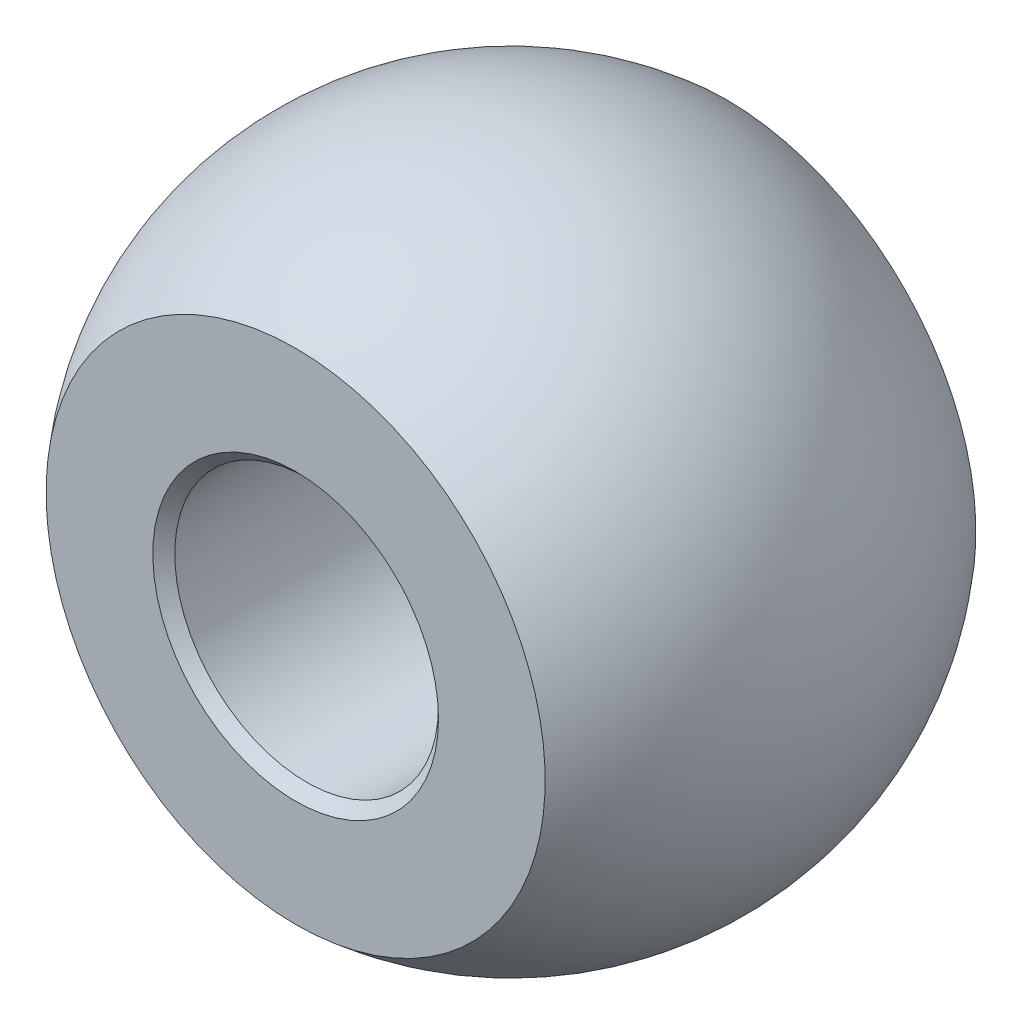
SolidWorks part; units mm, degrees
ref_plane "Front Plane" through (0, 0, 0) normal (0, 0, 1) x (1, 0, 0)
ref_plane "Top Plane" through (0, 0, 0) normal (0, 1, 0) x (1, 0, 0)
ref_plane "Right Plane" through (0, 0, 0) normal (1, 0, 0) x (0, 0, -1)
other "Center of Mass"
sketch "Sketch1" plane through (0, 0, 0) normal (0, 0, 1) x (1, 0, 0)
  line L0 (0, 0) -> (0, 7.5)
  arc A0 (0, 0) -> (0, 7.5) centre (0, 3.75) ccw
  dimension "D1" = 7.5
revolve "Revolve1" add sketch "Sketch1" angle 360 about L0
sketch "Sketch2" plane through (0, 0, 0) normal (1, 0, 0) x (0, 0, -1)
  line L0 (0, 0) -> (0, 1.219) construction
  line L1 (-4.45, 7.6) -> (-2.45, 7.6)
  line L2 (-4.45, 7.6) -> (-4.45, 0)
  line L3 (-4.45, 0) -> (-2.45, 0)
  line L4 (-2.45, 7.6) -> (-2.45, 0)
  line L5 (0.0734, 0) -> (5.1223, 0) construction
  line L6 (4.45, 0) -> (2.45, 0)
  line L7 (2.45, 7.6) -> (2.45, 0)
  line L8 (4.45, 7.6) -> (2.45, 7.6)
  line L9 (4.45, 7.6) -> (4.45, 0)
  dimension "D1" = 2.45
  dimension "D2" = 2
  dimension "D3" = 7.6
extrude "Cut-Extrude1" cut sketch "Sketch2" against normal through all both and the other way through all
sketch "Sketch3" plane through (0, 0, 2.45) normal (0, 0, 1) x (1, 0, 0)
  circle A0 centre (0, 3.75) radius 1.5
  circle A1 centre (0, 3.75) radius 2.839 construction
  dimension "D1" = 3
extrude "Cut-Extrude2" cut sketch "Sketch3" against normal through all both
chamfer "Chamfer1" distance 0.125 angle 45 2 edges at (1.5, 3.75, -2.45) (1.5, 3.75, 2.45)
ref_point "Point1"
